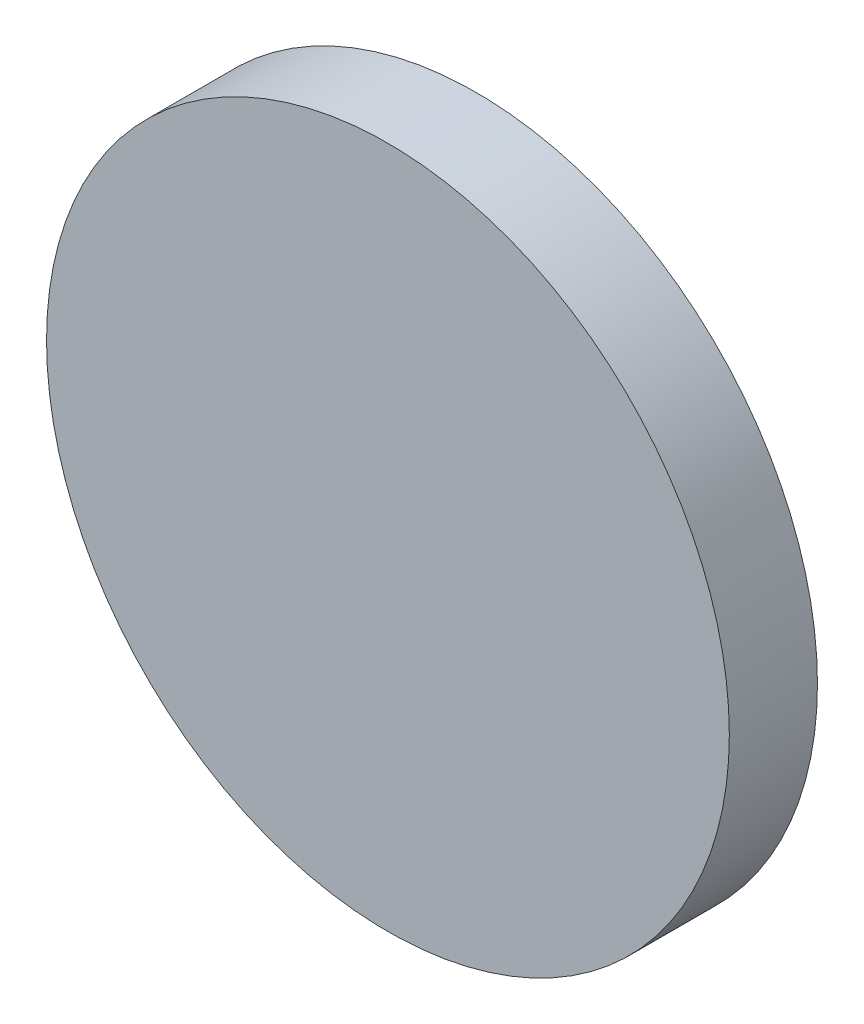
SolidWorks part; units mm, degrees
ref_plane "Front Plane" through (0, 0, 0) normal (0, 0, 1) x (1, 0, 0)
ref_plane "Top Plane" through (0, 0, 0) normal (0, 1, 0) x (1, 0, 0)
ref_plane "Right Plane" through (0, 0, 0) normal (1, 0, 0) x (0, 0, -1)
sketch "Sketch2" plane through (0, 0, 0) normal (0, 0, 1) x (1, 0, 0)
  circle A0 centre (4.0811, -9.6766) radius 9.8387
  dimension "D1" = 19.6774
extrude "Boss-Extrude1" add sketch "Sketch2" along normal blind 2.54
